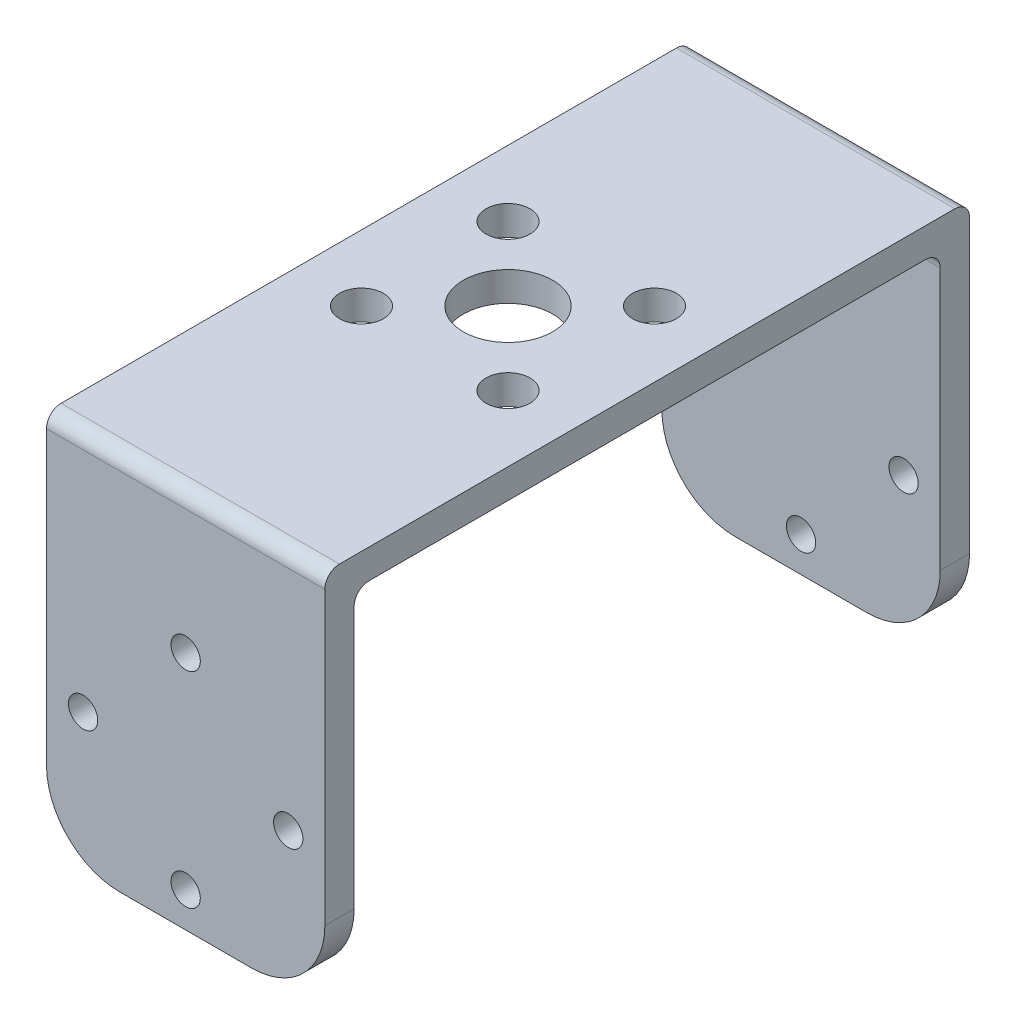
SolidWorks part; units mm, degrees
ref_plane "前视基准面" through (0, 0, 0) normal (0, 0, 1) x (1, 0, 0)
ref_plane "上视基准面" through (0, 0, 0) normal (0, 1, 0) x (1, 0, 0)
ref_plane "右视基准面" through (0, 0, 0) normal (1, 0, 0) x (0, 0, -1)
sketch "草图1" plane through (0, 0, 0) normal (1, 0, 0) x (0, 0, -1)
  line L0 (0, 29.2222) -> (0, -23.0741) construction
  line L1 (-20, -12.94) -> (-20, 10.94)
  line L2 (-22, 12.94) -> (22, 12.94)
  line L3 (-22, 12.94) -> (-22, -12.94)
  line L4 (-22, -12.94) -> (-20, -12.94)
  line L5 (22, 12.94) -> (22, -12.94)
  line L6 (-22, 12.94) -> (22, -12.94) construction
  line L7 (-22, -12.94) -> (22, 12.94) construction
  line L8 (-20, 10.94) -> (20, 10.94)
  line L9 (20, 10.94) -> (20, -12.94)
  line L10 (20, -12.94) -> (22, -12.94)
  point P3 (0, 0)
  dimension "D1" = 44
  dimension "D2" = 25.88
  dimension "D3" = 2
  dimension "D4" = 2
  dimension "D5" = 2
extrude "凸台-拉伸1" add sketch "草图1" along normal blind 19
fillet "圆角1" radius 1 4 edges at (9.5, 10.94, 20) (9.5, 12.94, 22) (9.5, 10.94, -20) (9.5, 12.94, -22)
sketch "草图2" plane through (0, 0, 22) normal (0, 0, 1) x (1, 0, 0)
  line L0 (9.5, 18.5694) -> (9.5, -19.8172) construction
  line L1 (-8.386, -3.56) -> (32.1992, -3.56) construction
  line L2 (0, 12.94) -> (19, 12.94) construction
  line L3 (19, 11.94) -> (19, -12.94) construction
  line L4 (0, 11.94) -> (0, -12.94) construction
  circle A0 centre (2.5, -3.56) radius 1
  circle A1 centre (16.5, -3.56) radius 1
  circle A2 centre (9.5, -10.56) radius 1
  circle A3 centre (9.5, 3.44) radius 1
  dimension "D2" = 2
  dimension "D3" = 23.5
  dimension "D4" = 9.5
  dimension "D5" = 2.5
  dimension "D6" = 2.5
  dimension "D1" = 16.5
extrude "切除-拉伸1" cut sketch "草图2" against normal blind 500000
fillet "圆角2" radius 5 2 edges at (19, -12.94, 21) (0, -12.94, 21)
fillet "圆角3" radius 5 2 edges at (0, -12.94, -21) (19, -12.94, -21)
sketch "草图3" plane through (0, 12.94, 0) normal (0, 1, 0) x (1, 0, 0)
  line L0 (-8.348, 0) -> (25.6687, 0) construction
  line L1 (9.5, 27.7679) -> (9.5, -34.5318) construction
  circle A0 centre (9.5, 0) radius 3.05
  circle A1 centre (4.5, 5) radius 1.5
  circle A2 centre (14.5, 5) radius 1.5
  circle A3 centre (14.5, -5) radius 1.5
  circle A4 centre (4.5, -5) radius 1.5
  dimension "D1" = 6.1
  dimension "D2" = 3
  dimension "D3" = 5
  dimension "D4" = 5
  dimension "D5" = 5
  dimension "D6" = 5
  dimension "D7" = 5
  dimension "D8" = 5
  dimension "D10" = 5
  dimension "D11" = 5
  dimension "D9" = 62.2997
extrude "切除-拉伸2" cut sketch "草图3" against normal blind 500
